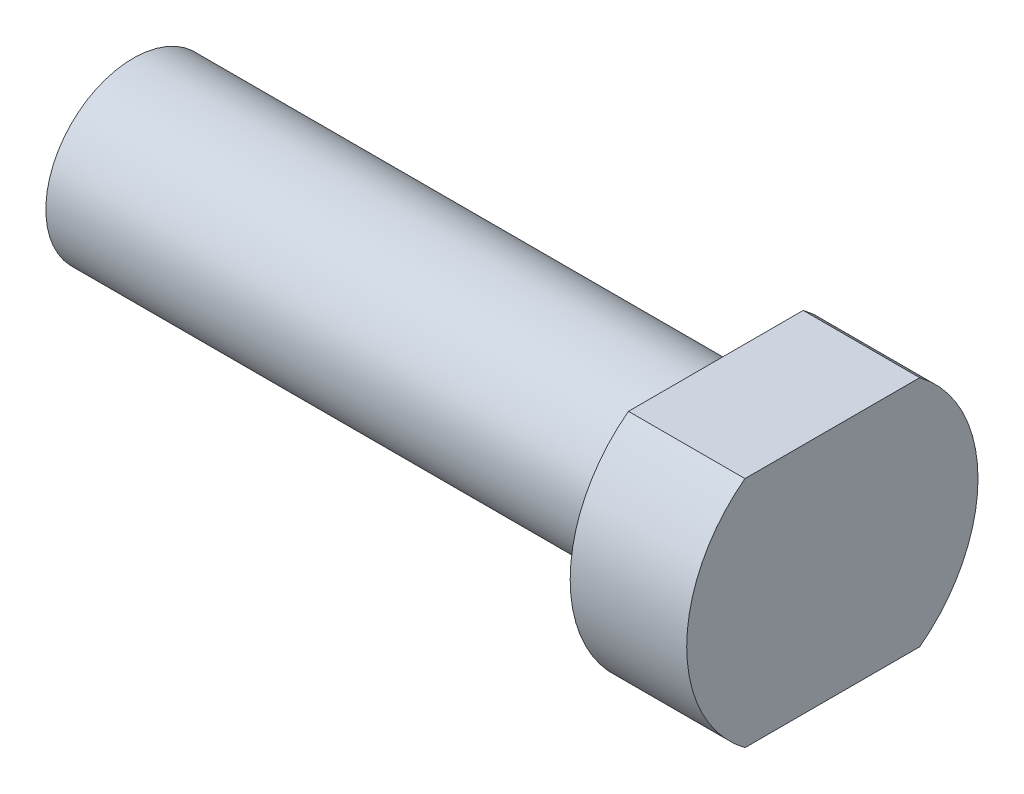
SolidWorks part; units mm, degrees
ref_plane "Front Plane" through (0, 0, 0) normal (0, 0, 1) x (1, 0, 0)
ref_plane "Top Plane" through (0, 0, 0) normal (0, 1, 0) x (1, 0, 0)
ref_plane "Right Plane" through (0, 0, 0) normal (1, 0, 0) x (0, 0, -1)
sketch "Sketch1" plane through (0, 0, 0) normal (0, 0, 1) x (1, 0, 0)
  line L0 (0, 0) -> (0, -1.5)
  line L1 (0, -1.5) -> (10, -1.5)
  line L2 (10, -1.5) -> (10, -2.5)
  line L5 (12, 0) -> (0, 0)
  line L6 (10, -2.5) -> (12, -2.5)
  line L7 (12, -2.5) -> (12, 0)
  dimension "D1" = 10
  dimension "D2" = 2
  dimension "D3" = 2.5
  dimension "D4" = 1.5
revolve "Revolve1" add sketch "Sketch1" angle 360 about L5
ref_plane "Plane1" through (0, 3, 0) normal (0, 1, 0) x (1, 0, 0)
sketch "Sketch2" plane through (0, 3, 0) normal (0, 1, 0) x (1, 0, 0)
  line L1 (10, 2.5) -> (12, 2.5)
  line L2 (10, 2.5) -> (10, -2.5)
  line L3 (10, -2.5) -> (12, -2.5)
  line L4 (12, 2.5) -> (12, -2.5)
extrude "Cut-Extrude1" cut sketch "Sketch2" against normal blind 1
ref_plane "Plane2" through (0, -3, 0) normal (0, 1, 0) x (1, 0, 0)
sketch "Sketch4" plane through (0, -3, 0) normal (0, 1, 0) x (1, 0, 0)
  line L1 (10, 1.5) -> (12, 1.5)
  line L2 (10, 1.5) -> (10, -1.5)
  line L3 (10, -1.5) -> (12, -1.5)
  line L4 (12, 1.5) -> (12, -1.5)
extrude "Cut-Extrude2" cut sketch "Sketch4" along normal blind 1
